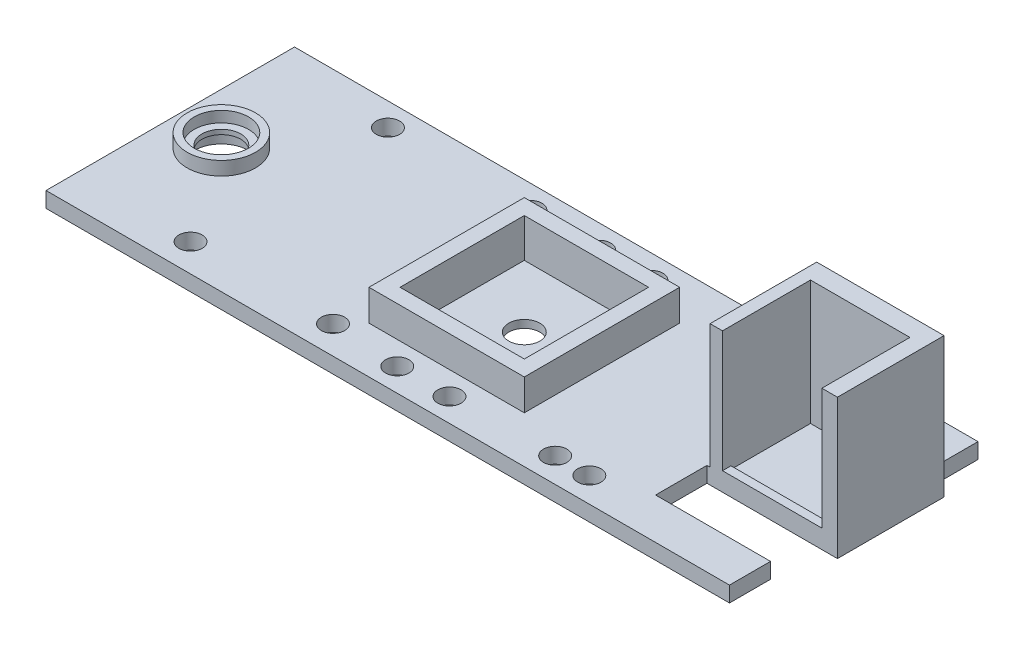
SolidWorks part; units mm, degrees
ref_plane "Front Plane" through (0, 0, 0) normal (0, 0, 1) x (1, 0, 0)
ref_plane "Top Plane" through (0, 0, 0) normal (0, 1, 0) x (1, 0, 0)
ref_plane "Right Plane" through (0, 0, 0) normal (1, 0, 0) x (0, 0, -1)
sketch "Sketch1" plane through (0, 0, 0) normal (0, 1, 0) x (1, 0, 0)
  line L1 (-279.4, -50.8) -> (0, -50.8)
  line L2 (-279.4, -50.8) -> (-279.4, 50.8)
  line L3 (-279.4, 50.8) -> (0, 50.8)
  line L4 (0, -50.8) -> (0, 50.8)
  point P0 (0, 0)
  dimension "D1" = 279.4
  dimension "D2" = 101.6
  dimension "D3" = 50.8
extrude "Boss-Extrude1" add sketch "Sketch1" along normal blind 6.35
sketch "Sketch2" plane through (0, 6.35, 0) normal (0, 1, 0) x (1, 0, 0)
  line L0 (-279.4, 50.8) -> (-279.4, -50.8) construction
  line L2 (0, 50.8) -> (-279.4, 50.8) construction
  circle A0 centre (-258.5106, 0) radius 13.97
  dimension "D1" = 50.8
  dimension "D2" = 27.94
  dimension "D3" = 20.8894
extrude "Boss-Extrude3" add sketch "Sketch2" along normal blind 5.5562
sketch "Sketch9" plane through (0, 11.9062, 0) normal (0, 1, 0) x (1, 0, 0)
  circle A0 centre (-258.5106, 0) radius 11.1125
  dimension "D1" = 22.225
extrude "Cut-Extrude4" cut sketch "Sketch9" against normal blind 4.445
sketch "Sketch10" plane through (0, 0, 0) normal (0, -1, 0) x (-1, 0, 0)
  circle A0 centre (258.5106, 0) radius 11.1125
  dimension "D1" = 22.225
extrude "Cut-Extrude5" cut sketch "Sketch10" against normal blind 5.5562
sketch "Sketch11" plane through (0, 7.4613, 0) normal (0, 1, 0) x (1, 0, 0)
  circle A0 centre (-258.5106, 0) radius 7.9375
  dimension "D1" = 15.875
extrude "Cut-Extrude6" cut sketch "Sketch11" against normal through all
sketch "Sketch12" plane through (0, 6.35, 0) normal (0, 1, 0) x (1, 0, 0)
  line L0 (0, 50.8) -> (-279.4, 50.8) construction
  line L1 (-279.4, 50.8) -> (-279.4, -50.8) construction
  circle A0 centre (-134.6662, 0) radius 6.35
  dimension "D1" = 12.7
  dimension "D2" = 50.8
  dimension "D3" = 144.7338
extrude "Cut-Extrude7" cut sketch "Sketch12" against normal through all
sketch "Sketch22" plane through (0, 6.35, 0) normal (0, 1, 0) x (1, 0, 0)
  line L1 (-102.9162, -31.75) -> (-166.4162, -31.75)
  line L2 (-102.9162, -31.75) -> (-102.9162, 31.75)
  line L3 (-102.9162, 31.75) -> (-166.4162, 31.75)
  line L4 (-166.4162, -31.75) -> (-166.4162, 31.75)
  line L5 (-102.9162, -31.75) -> (-166.4162, 31.75) construction
  line L6 (-102.9162, 31.75) -> (-166.4162, -31.75) construction
  circle A0 centre (-134.6662, 0) radius 6.35 construction
  point P0 (-134.6662, 0)
  dimension "D1" = 63.5
  dimension "D2" = 63.5
extrude "Boss-Extrude7" add sketch "Sketch22" along normal blind 12.7
sketch "Sketch25" plane through (0, 19.05, 0) normal (0, 1, 0) x (1, 0, 0)
  line L1 (-109.2662, -25.4) -> (-160.0662, -25.4)
  line L2 (-109.2662, -25.4) -> (-109.2662, 25.4)
  line L3 (-109.2662, 25.4) -> (-160.0662, 25.4)
  line L4 (-160.0662, -25.4) -> (-160.0662, 25.4)
  line L5 (-109.2662, -25.4) -> (-160.0662, 25.4) construction
  line L6 (-109.2662, 25.4) -> (-160.0662, -25.4) construction
  circle A0 centre (-134.6662, 0) radius 6.35 construction
  point P0 (-134.6662, 0)
  dimension "D1" = 50.8
  dimension "D2" = 50.8
extrude "Cut-Extrude11" cut sketch "Sketch25" against normal blind 15.875
sketch "Sketch32" plane through (0, 6.35, 0) normal (0, 1, 0) x (1, 0, 0)
  line L0 (0, -50.8) -> (0, 50.8) construction
  line L3 (-279.4, -50.8) -> (0, -50.8) construction
  line L5 (0, 50.8) -> (-279.4, 50.8) construction
  circle A0 centre (-67.442, -40.64) radius 4.7625
  circle A1 centre (-81.412, -40.64) radius 4.7625
  circle A2 centre (-67.442, 40.64) radius 4.7625
  circle A3 centre (-81.412, 40.64) radius 4.7625
  dimension "D1" = 10.16
  dimension "D2" = 10.16
  dimension "D3" = 10.16
  dimension "D4" = 10.16
  dimension "D9" = 9.525
  dimension "D10" = 9.525
  dimension "D11" = 9.525
  dimension "D12" = 9.525
  dimension "D5" = 13.97
  dimension "D6" = 13.97
  dimension "D7" = 81.28
  dimension "D8" = 81.412
extrude "Cut-Extrude12" cut sketch "Sketch32" against normal blind 6.35
sketch "Sketch38" plane through (0, 6.35, 0) normal (0, 1, 0) x (1, 0, 0)
  line L0 (0, -50.8) -> (0, 50.8) construction
  line L1 (0, -34.0128) -> (-46.99, -34.0128)
  line L2 (0, -34.0128) -> (0, -15.5426)
  line L3 (0, -15.5426) -> (-46.99, -15.5426)
  line L4 (-46.99, -34.0128) -> (-46.99, -15.5426)
  line L6 (-279.4, -50.8) -> (0, -50.8) construction
  dimension "D1" = 35.2574
  dimension "D2" = 18.4703
  dimension "D3" = 46.99
extrude "Cut-Extrude13" cut sketch "Sketch38" against normal blind 6.35
sketch "Sketch60" plane through (0, 6.35, 0) normal (0, 1, 0) x (1, 0, 0)
  line L1 (-279.4, 50.8) -> (-279.4, -50.8) construction
  line L2 (0, 50.8) -> (-279.4, 50.8) construction
  circle A0 centre (-231.7492, 41.3241) radius 4.7625
  circle A1 centre (-231.7492, -39.3693) radius 4.7625
  circle A2 centre (-173.5092, -39.3693) radius 4.7625
  circle A3 centre (-173.5092, 41.3241) radius 4.7625
  dimension "D1" = 47.6508
  dimension "D5" = 9.525
  dimension "D6" = 9.525
  dimension "D7" = 9.525
  dimension "D8" = 9.525
  dimension "D2" = 58.24
  dimension "D3" = 80.6935
  dimension "D4" = 9.4759
  dimension "D9" = 105.8908
extrude "Cut-Extrude23" cut sketch "Sketch60" against normal up to surface (6.35 mm away) up to face at (-81.5975, 0, 12.3889)
sketch "Sketch64" plane through (0, 6.35, 0) normal (0, 1, 0) x (1, 0, 0)
  line L0 (-279.4, -50.8) -> (0, -50.8) construction
  circle A0 centre (-145.3342, -41.275) radius 4.7625
  circle A1 centre (-123.9982, -41.275) radius 4.7625
  circle A3 centre (-134.6662, 0) radius 6.35 construction
  dimension "D1" = 21.336
  dimension "D3" = 9.525
  dimension "D4" = 9.525
  dimension "D2" = 10.668
  dimension "D5" = 9.525
  dimension "D6" = 9.525
extrude "Cut-Extrude24" cut sketch "Sketch64" against normal through all
mirror "Mirror1" about plane through (0, 0, 0) normal (0, 0, 1) of "Cut-Extrude24"
sketch "Sketch65" plane through (0, 6.35, 0) normal (0, 1, 0) x (1, 0, 0)
  line L0 (-46.99, -34.0128) -> (0, -34.0128) construction
  line L1 (-45.72, -13.0128) -> (6.35, -13.0128)
  line L2 (-45.72, -13.0128) -> (-45.72, 30.5839)
  line L3 (-45.72, 30.5839) -> (6.35, 30.5839)
  line L4 (6.35, -13.0128) -> (6.35, 30.5839)
  line L5 (0, -15.5426) -> (0, 50.8) construction
  dimension "D1" = 6.35
  dimension "D2" = 52.07
  dimension "D3" = 64.5968
  dimension "D4" = 43.5968
extrude "Boss-Extrude8" add sketch "Sketch65" along normal blind 50.8
sketch "Sketch66" plane through (0, 57.15, 0) normal (0, 1, 0) x (1, 0, 0)
  line L0 (-45.72, -13.0128) -> (6.35, -13.0128) construction
  line L1 (-40.64, -9.5361) -> (0, -9.5361)
  line L2 (-40.64, -9.5361) -> (-40.64, 22.9639)
  line L3 (-40.64, 22.9639) -> (0, 22.9639)
  line L4 (0, -9.5361) -> (0, 22.9639)
  line L5 (6.35, -13.0128) -> (6.35, 30.5839) construction
  line L6 (-45.72, 30.5839) -> (-45.72, -13.0128) construction
  line L7 (6.35, 30.5839) -> (-45.72, 30.5839) construction
  dimension "D1" = 3.4768
  dimension "D2" = 6.35
  dimension "D3" = 5.08
  dimension "D4" = 7.62
sketch "Sketch68" plane through (0, 0, 0) normal (1, 0, 0) x (0, 0, -1)
  line L0 (30.5839, 57.15) -> (30.5839, 6.35) construction
  line L1 (-13.0128, 6.35) -> (30.5839, 6.35)
  line L2 (-13.0128, 6.35) -> (-13.0128, 0)
  line L3 (-13.0128, 0) -> (30.5839, 0)
  line L4 (30.5839, 6.35) -> (30.5839, 0)
  line L5 (-13.0128, 57.15) -> (-13.0128, 6.35) construction
  line L7 (-15.5426, 0) -> (50.8, 0) construction
  dimension "D1" = 6.35
extrude "Boss-Extrude10" add sketch "Sketch68" along normal up to surface (6.35 mm away) up to face at (6.35, 31.75, -8.7856)
extrude "Cut-Extrude28" cut sketch "Sketch66" against normal blind 50.8
sketch "Sketch69" plane through (0, 0, 9.5361) normal (0, 0, -1) x (-1, 0, 0)
  line L0 (40.64, 6.35) -> (40.64, 57.15) construction
  line L1 (0, 57.15) -> (40.64, 57.15)
  line L2 (0, 57.15) -> (0, 7.62)
  line L3 (0, 7.62) -> (40.64, 7.62)
  line L4 (40.64, 57.15) -> (40.64, 7.62)
  line L5 (40.64, 6.35) -> (0, 6.35) construction
  dimension "D1" = 1.27
extrude "Cut-Extrude29" cut sketch "Sketch69" against normal through all
sketch "Sketch70" plane through (0, 6.35, 0) normal (0, 1, 0) x (1, 0, 0)
  line L1 (-46.99, -15.5426) -> (0, -15.5426)
  line L2 (-46.99, -15.5426) -> (-46.99, -13.0128)
  line L3 (-46.99, -13.0128) -> (0, -13.0128)
  line L4 (0, -15.5426) -> (0, -13.0128)
extrude "Cut-Extrude30" cut sketch "Sketch70" against normal through all
